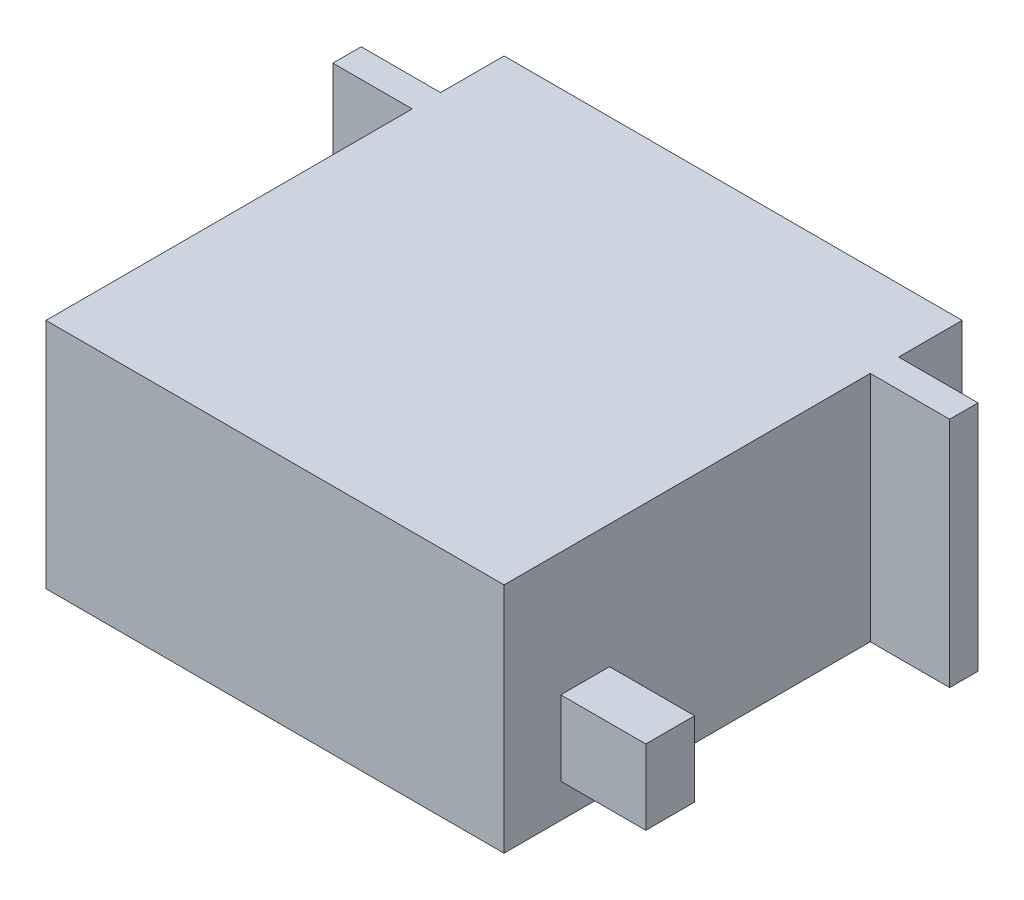
SolidWorks part; units mm, degrees
ref_plane "Front Plane" through (0, 0, 0) normal (0, 0, 1) x (1, 0, 0)
ref_plane "Top Plane" through (0, 0, 0) normal (0, 1, 0) x (1, 0, 0)
ref_plane "Right Plane" through (0, 0, 0) normal (1, 0, 0) x (0, 0, -1)
sketch "Sketch2" plane through (0, 0, 0) normal (0, 1, 0) x (1, 0, 0)
  line L0 (-2.4547, 12.0637) -> (-2.4547, -28.3363) construction
  line L1 (-22.6547, 12.0637) -> (17.7453, 12.0637)
  line L2 (-22.6547, 12.0637) -> (-22.6547, -28.3363)
  line L3 (-22.6547, -28.3363) -> (17.7453, -28.3363)
  line L4 (17.7453, 12.0637) -> (17.7453, -28.3363)
  line L5 (24.7453, 6.4637) -> (17.7453, 6.4637)
  line L6 (24.7453, 6.4637) -> (24.7453, 3.9637)
  line L7 (24.7453, 3.9637) -> (17.7453, 3.9637)
  line L8 (17.7453, 6.4637) -> (17.7453, 3.9637)
  line L9 (-29.6547, 6.4637) -> (-22.6547, 6.4637)
  line L10 (-29.6547, 6.4637) -> (-29.6547, 3.9637)
  line L11 (-29.6547, 3.9637) -> (-22.6547, 3.9637)
  line L12 (17.7453, 6.4637) -> (17.7453, 3.9637)
  line L13 (-22.6547, 6.4637) -> (-22.6547, 3.9637)
  point P14 (0, 0)
  dimension "D1" = 40.4
  dimension "D2" = 2.5
  dimension "D3" = 7
  dimension "D4" = 0
  dimension "D5" = 5.6
extrude "Boss-Extrude3" add sketch "Sketch2" along normal blind 20.5 contours L10 L11 L2 L9 | L0 L1 L2 L3 | L1 L0 L3 L4 | L7 L6 L5 L4
sketch "Sketch4" plane through (17.7453, 0, 0) normal (1, 0, 0) x (0, 0, -1)
  line L0 (3.9637, 0) -> (-28.3363, 0) construction
  line L1 (-19.0363, 9.6) -> (-23.3363, 9.6)
  line L2 (-19.0363, 9.6) -> (-19.0363, 3)
  line L3 (-19.0363, 3) -> (-23.3363, 3)
  line L4 (-23.3363, 9.6) -> (-23.3363, 3)
  line L5 (-28.3363, 20.5) -> (-28.3363, 0) construction
  dimension "D1" = 6.6
  dimension "D2" = 4.3
  dimension "D3" = 3
  dimension "D4" = 5
extrude "Wire" add sketch "Sketch4" along normal blind 7.5
sketch "Sketch6" plane through (0, 0, -12.0637) normal (0, 0, -1) x (-1, 0, 0)
  line L0 (-17.7453, 20.5) -> (-17.7453, 0) construction
  line L1 (22.6547, 20.5) -> (-17.7453, 20.5) construction
  circle A0 centre (-8.2453, 11) radius 3
  dimension "D1" = 6
  dimension "D2" = 9.5
  dimension "D3" = 9.5
extrude "Boss-Extrude5" add sketch "Sketch6" along normal blind 6.4
